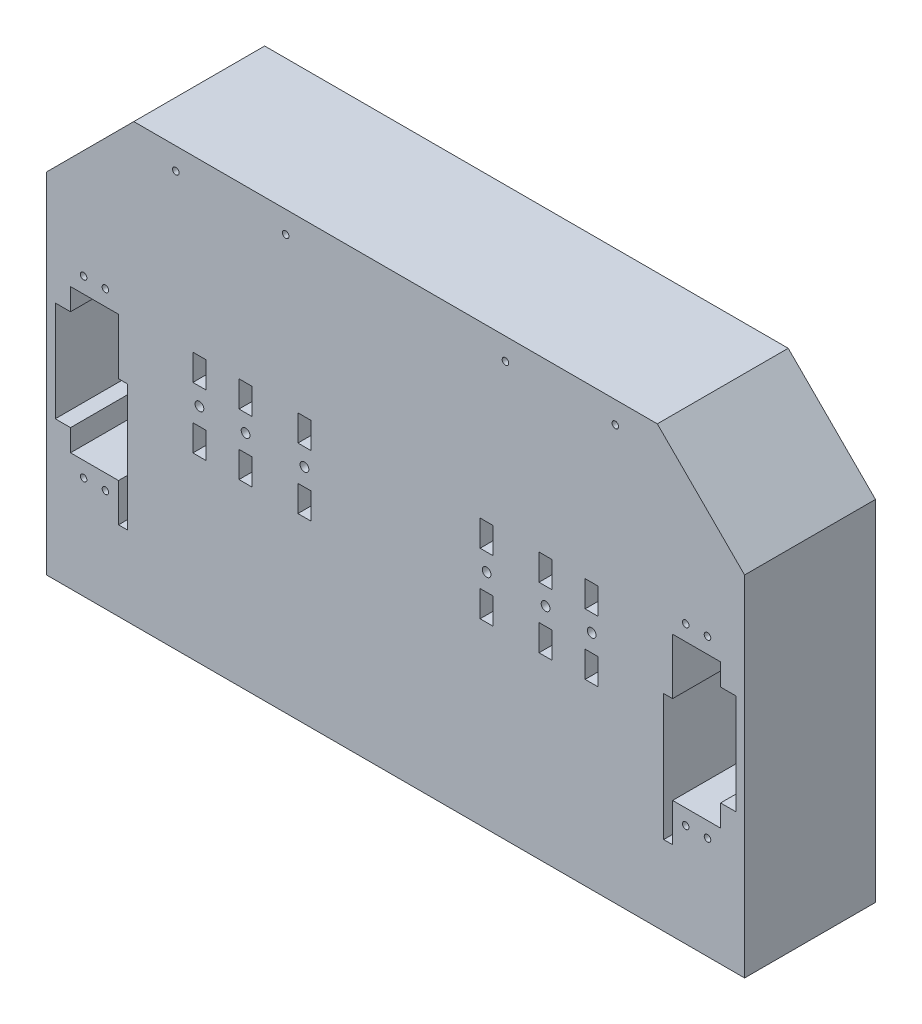
SolidWorks part; units mm, degrees
ref_plane "Plan de face" through (0, 0, 0) normal (0, 0, 1) x (1, 0, 0)
ref_plane "Plan de dessus" through (0, 0, 0) normal (0, 1, 0) x (1, 0, 0)
ref_plane "Plan de droite" through (0, 0, 0) normal (1, 0, 0) x (0, 0, -1)
sketch "Esquisse1" plane through (0, 0, 0) normal (0, 0, 1) x (1, 0, 0)
  line L1 (0, 0) -> (-320, 0)
  line L2 (0, 0) -> (0, 200)
  line L3 (0, 200) -> (-320, 200)
  line L4 (-320, 0) -> (-320, 200)
  dimension "D1" = 320
  dimension "D2" = 200
extrude "Boss.-Extru.1" add sketch "Esquisse1" along normal blind 60
sketch "Esquisse3" plane through (0, 0, 0) normal (0, 0, -1) x (-1, 0, 0)
  line L0 (-99.1135, 102) -> (419.1135, 102) construction
  line L1 (73.1, 82) -> (73.1, 94)
  line L2 (67.1, 122) -> (73.1, 122)
  line L3 (67.1, 122) -> (67.1, 110)
  line L4 (67.1, 110) -> (73.1, 110)
  line L5 (73.1, 122) -> (73.1, 110)
  line L6 (67.1, 94) -> (73.1, 94)
  line L7 (67.1, 82) -> (67.1, 94)
  line L8 (67.1, 82) -> (73.1, 82)
  line L9 (94.24, 82) -> (94.24, 94)
  line L10 (88.24, 122) -> (94.24, 122)
  line L11 (88.24, 122) -> (88.24, 110)
  line L12 (88.24, 110) -> (94.24, 110)
  line L13 (94.24, 122) -> (94.24, 110)
  line L14 (88.24, 94) -> (94.24, 94)
  line L15 (88.24, 82) -> (88.24, 94)
  line L16 (88.24, 82) -> (94.24, 82)
  line L17 (121.24, 82) -> (121.24, 94)
  line L18 (115.24, 122) -> (121.24, 122)
  line L19 (115.24, 122) -> (115.24, 110)
  line L20 (115.24, 110) -> (121.24, 110)
  line L21 (121.24, 122) -> (121.24, 110)
  line L22 (115.24, 94) -> (121.24, 94)
  line L23 (115.24, 82) -> (115.24, 94)
  line L24 (115.24, 82) -> (121.24, 82)
  line L25 (160, 102) -> (160, 9.4958) construction
  line L26 (204.76, 82) -> (198.76, 82)
  line L27 (204.76, 82) -> (204.76, 94)
  line L28 (204.76, 94) -> (198.76, 94)
  line L29 (198.76, 122) -> (198.76, 110)
  line L30 (204.76, 110) -> (198.76, 110)
  line L31 (204.76, 122) -> (204.76, 110)
  line L32 (204.76, 122) -> (198.76, 122)
  line L33 (198.76, 82) -> (198.76, 94)
  line L34 (231.76, 82) -> (225.76, 82)
  line L35 (231.76, 82) -> (231.76, 94)
  line L36 (231.76, 94) -> (225.76, 94)
  line L37 (225.76, 122) -> (225.76, 110)
  line L38 (231.76, 110) -> (225.76, 110)
  line L39 (231.76, 122) -> (231.76, 110)
  line L40 (231.76, 122) -> (225.76, 122)
  line L41 (225.76, 82) -> (225.76, 94)
  line L42 (252.9, 82) -> (246.9, 82)
  line L43 (252.9, 82) -> (252.9, 94)
  line L44 (252.9, 94) -> (246.9, 94)
  line L45 (246.9, 122) -> (246.9, 110)
  line L46 (252.9, 110) -> (246.9, 110)
  line L47 (252.9, 122) -> (252.9, 110)
  line L48 (252.9, 122) -> (246.9, 122)
  line L49 (246.9, 82) -> (246.9, 94)
  line L50 (70.1, 110) -> (70.1, 94) construction
  line L51 (91.24, 110) -> (91.24, 94) construction
  line L52 (118.24, 110) -> (118.24, 94) construction
  line L53 (67.1, 82) -> (0, 82) construction
  line L54 (0, 0) -> (0, 200) construction
  line L55 (252.9, 82) -> (320, 82) construction
  line L56 (320, 200) -> (320, 0) construction
  line L57 (0, 200) -> (320, 200) construction
  circle A0 centre (70.1, 102) radius 2
  circle A1 centre (91.24, 102) radius 2
  circle A2 centre (118.24, 102) radius 2
  circle A3 centre (201.76, 102) radius 2
  circle A4 centre (228.76, 102) radius 2
  circle A5 centre (249.9, 102) radius 2
  dimension "D4" = 4
  dimension "D5" = 4
  dimension "D6" = 4
  dimension "D1" = 6
  dimension "D2" = 12
  dimension "D3" = 8
  dimension "D7" = 15.14
  dimension "D8" = 21
  dimension "D9" = 89.9
  dimension "D10" = 78
extrude "Enlèv. mat.-Extru.2" cut sketch "Esquisse3" against normal blind 60
chamfer "Chanfrein1" distance 40 angle 45 2 edges at (-320, 200, 30) (0, 200, 30)
sketch "Esquisse6" plane through (0, 0, 60) normal (0, 0, 1) x (1, 0, 0)
  line L0 (-287, 120) -> (-309, 120)
  line L1 (-287, 120) -> (-287, 94.4057)
  line L2 (-287, 54) -> (-309, 54)
  line L3 (-316, 110) -> (-316, 64)
  line L4 (-160, 175.4057) -> (-160, -53.1633) construction
  line L5 (-259.5212, 87.0745) -> (-238.5212, 87.0745) construction
  line L6 (-33, 36.4057) -> (-33, 54)
  line L7 (-37.1, 94.4057) -> (-37.1, 36.4057)
  line L8 (-33, 36.4057) -> (-37.1, 36.4057)
  line L9 (-33, 94.4057) -> (-37.1, 94.4057)
  line L10 (-295.1422, 117.2394) -> (-276.6212, 109.6914) construction
  line L11 (-233.6255, 168.9553) -> (-271.8158, 198.5542) construction
  line L12 (-260.7502, 189.978) -> (-160, 189.978) construction
  line L13 (-11, 54) -> (-11, 64)
  line L14 (-4, 64) -> (-11, 64)
  line L15 (-11, 120) -> (-11, 110)
  line L16 (-316, 110) -> (-309, 110)
  line L17 (-309, 120) -> (-309, 110)
  line L18 (-4, 110) -> (-11, 110)
  line L19 (-316, 64) -> (-309, 64)
  line L20 (-309, 54) -> (-309, 64)
  line L21 (-287, 94.4057) -> (-282.9, 94.4057)
  line L22 (-287, 36.4057) -> (-282.9, 36.4057)
  line L23 (-282.9, 94.4057) -> (-282.9, 36.4057)
  line L24 (-287, 36.4057) -> (-287, 54)
  line L25 (-4, 110) -> (-4, 64)
  line L26 (-33, 54) -> (-11, 54)
  line L27 (-33, 120) -> (-33, 94.4057)
  line L28 (-33, 120) -> (-11, 120)
  line L29 (-298, 54) -> (-298, 47) construction
  line L30 (-303, 54) -> (-293, 54) construction
  line L31 (-303, 54) -> (-303, 47) construction
  line L32 (-303, 47) -> (-293, 47) construction
  line L33 (-293, 54) -> (-293, 47) construction
  line L34 (-316, 87) -> (-320, 87) construction
  line L35 (-320, 160) -> (-320, 0) construction
  line L36 (-4, 87) -> (0, 87) construction
  line L37 (0, 0) -> (0, 160) construction
  line L38 (-228.76, 100) -> (-116.24, 102) construction
  line L39 (-298, 120) -> (-298, 54) construction
  line L40 (-116.24, 102) -> (-320, 98.3782) construction
  line L41 (-40, 200) -> (-280, 200) construction
  circle A0 centre (-260.7502, 189.978) radius 1.5
  circle A1 centre (-210.3751, 189.978) radius 1.5
  circle A2 centre (-109.6249, 189.978) radius 1.5
  circle A3 centre (-59.2498, 189.978) radius 1.5
  circle A4 centre (-303, 47) radius 1.5
  circle A5 centre (-200, -20.7633) radius 1.5
  circle A6 centre (-120, -20.7633) radius 1.5
  circle A7 centre (-293, 47) radius 1.5
  circle A8 centre (-293, 127.1489) radius 1.5
  circle A9 centre (-303, 127.1489) radius 1.5
  circle A10 centre (-27, 47) radius 1.5
  circle A11 centre (-17, 47) radius 1.5
  circle A12 centre (-17, 127.1489) radius 1.5
  circle A13 centre (-27, 127.1489) radius 1.5
  circle A14 centre (-228.76, 102) radius 2 construction
  circle A15 centre (-118.24, 102) radius 2 construction
  point P65 (-232.6941, 65.194)
  point P66 (-316, 87)
  point P71 (-4, 87)
  point P83 (-298, 87)
  dimension "D2" = 3
  dimension "D4" = 3
  dimension "D5" = 3
  dimension "D14" = 3
  dimension "D15" = 3
  dimension "D1" = 66
  dimension "D3" = 14
  dimension "D6" = 40
  dimension "D7" = 32.4
  dimension "D8" = 7
  dimension "D9" = 10
  dimension "D10" = 10
  dimension "D11" = 22
  dimension "D12" = 7
  dimension "D13" = 10
  dimension "D16" = 33.1
  dimension "D17" = 69.978
  dimension "D18" = 22.1498
  dimension "D19" = 82.9
  dimension "D20" = 7.1489
  dimension "D21" = 80
extrude "Enlèv. mat.-Extru.3" cut sketch "Esquisse6" against normal blind 60 contours L23 L22 L24 L2 L20 L19 L3 L16 L17 L0 L1 L21 | L27 L9 L7 L8 L6 L26 L13 L14 L25 L18 L15 L28
